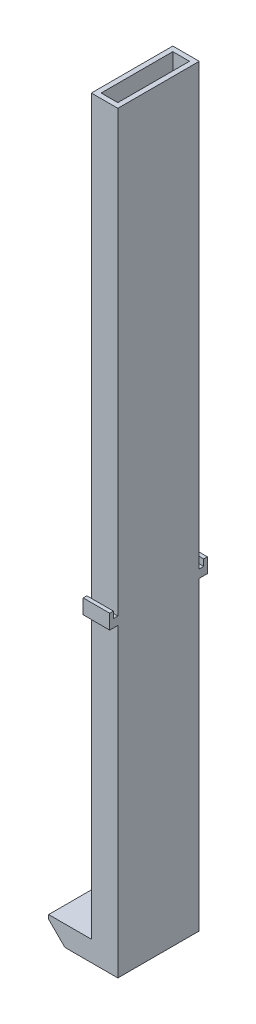
SolidWorks part; units mm, degrees
ref_plane "Front Plane" through (0, 0, 0) normal (0, 0, 1) x (1, 0, 0)
ref_plane "Top Plane" through (0, 0, 0) normal (0, 1, 0) x (1, 0, 0)
ref_plane "Right Plane" through (0, 0, 0) normal (1, 0, 0) x (0, 0, -1)
sketch "Sketch1" plane through (0, 0, 0) normal (0, 0, 1) x (1, 0, 0)
  line L1 (-4.25, -46.25) -> (4.25, -46.25)
  line L2 (-4.25, -46.25) -> (-4.25, 46.25)
  line L3 (-4.25, 46.25) -> (4.25, 46.25)
  line L4 (4.25, -46.25) -> (4.25, 46.25)
  line L5 (-4.25, -46.25) -> (4.25, 46.25) construction
  line L6 (-4.25, 46.25) -> (4.25, -46.25) construction
  point P0 (0, 0)
  dimension "D1" = 8.5
  dimension "D2" = 92.5
extrude "Boss-Extrude1" add sketch "Sketch1" along normal blind 10 contours L3 L4 L1 L2
sketch "Sketch2" plane through (0, 0, 10) normal (0, 0, 1) x (1, 0, 0)
  line L0 (-4.25, -46.25) -> (4.25, -46.25) construction
  line L1 (-4.25, 46.25) -> (1, 46.25)
  line L2 (-4.25, 46.25) -> (-4.25, -43.75)
  line L3 (-4.25, -43.75) -> (1, -43.75)
  line L4 (1, 46.25) -> (1, -43.75)
  dimension "D1" = 2.5
  dimension "D2" = 5.25
extrude "Cut-Extrude3" cut sketch "Sketch2" against normal blind 80 contours L1 L4 L3 L2
chamfer "Chamfer1" distance 2 1 edges at (-4.25, -46.25, 5)
sketch "Sketch7" plane through (1, 0, 0) normal (-1, 0, 0) x (0, 0, 1)
  line L1 (10, 46.25) -> (10, -43.75) construction
  line L2 (10, -8.75) -> (11, -8.75)
  line L3 (11, -8.75) -> (11, -6.95)
  line L4 (11, -6.95) -> (10.55, -6.95)
  line L5 (10.55, -6.95) -> (10.55, -7.75)
  line L6 (10.55, -7.75) -> (10, -7.75)
  line L7 (10, -7.75) -> (10, -8.75)
  dimension "D1" = 37.5
  dimension "D2" = 1
  dimension "D3" = 1.8
  dimension "D4" = 0.45
  dimension "D5" = 1
extrude "Boss-Extrude3" add sketch "Sketch7" against normal blind 3.25
ref_plane "Plane2" through (0, 0, 5) normal (0, 0, 1) x (1, 0, 0)
mirror "Mirror2" about plane through (0, 0, 5) normal (0, 0, 1) of "Boss-Extrude3"
sketch "Sketch9" plane through (0, 46.25, 0) normal (0, 1, 0) x (1, 0, 0)
  line L0 (2.625, 0) -> (2.625, -10) construction
  line L1 (1, 0) -> (4.25, 0) construction
  line L2 (4.25, -10) -> (1, -10) construction
  line L3 (4.25, 0) -> (1, 0) construction
  line L4 (1.6, -9.4) -> (3.65, -9.4)
  line L5 (1.6, -9.4) -> (1.6, -0.6)
  line L6 (1.6, -0.6) -> (3.65, -0.6)
  line L7 (3.65, -9.4) -> (3.65, -0.6)
  line L8 (1.6, -9.4) -> (3.65, -0.6) construction
  line L9 (1.6, -0.6) -> (3.65, -9.4) construction
  line L10 (4.25, -10) -> (4.25, 0) construction
  point P6 (2.625, -5)
  dimension "D1" = 0.6
  dimension "D2" = 0.6
extrude "Cut-Extrude4" cut sketch "Sketch9" against normal blind 80
